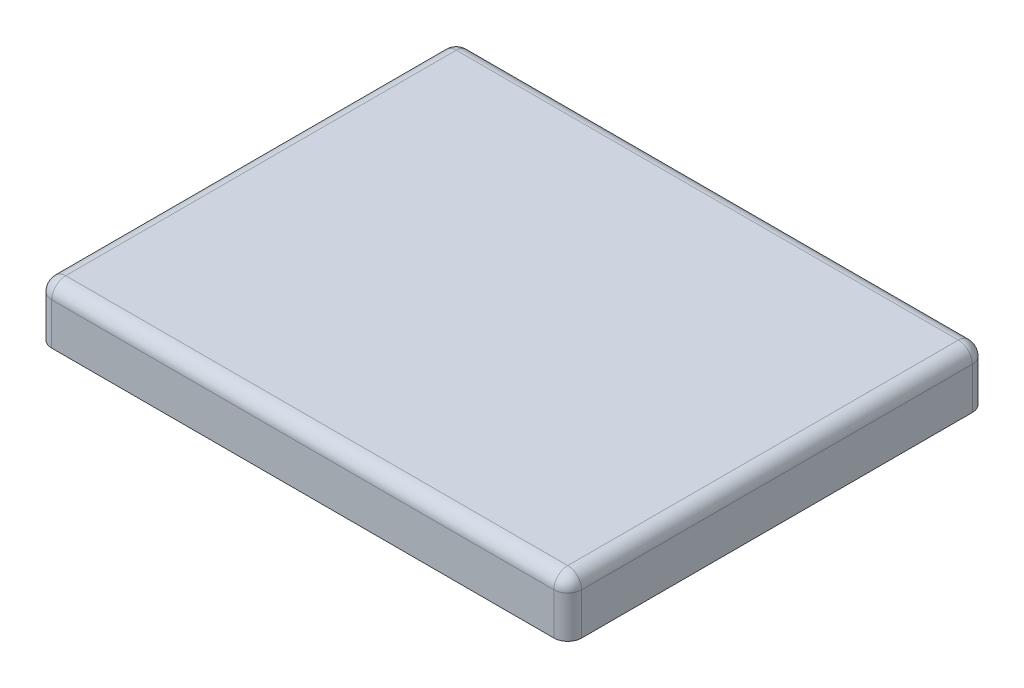
SolidWorks part; units mm, degrees
ref_plane "Front Plane" through (0, 0, 0) normal (0, 0, 1) x (1, 0, 0)
ref_plane "Top Plane" through (0, 0, 0) normal (0, 1, 0) x (1, 0, 0)
ref_plane "Right Plane" through (0, 0, 0) normal (1, 0, 0) x (0, 0, -1)
sketch "Sketch1" plane through (0, 0, 0) normal (0, 1, 0) x (1, 0, 0)
  line L1 (0, 0) -> (482.6, 0)
  line L2 (0, 0) -> (0, 381)
  line L3 (0, 381) -> (482.6, 381)
  line L4 (482.6, 0) -> (482.6, 381)
  dimension "D1" = 482.6
  dimension "D2" = 381
extrude "Boss-Extrude1" add sketch "Sketch1" along normal blind 50.8
fillet "Fillet1" radius 12.7 8 edges at (0, 25.4, -381) (482.6, 25.4, -381) (241.3, 50.8, -381) (0, 50.8, -190.5) (0, 25.4, 0) (241.3, 50.8, 0) (482.6, 50.8, -190.5) (482.6, 25.4, 0)
